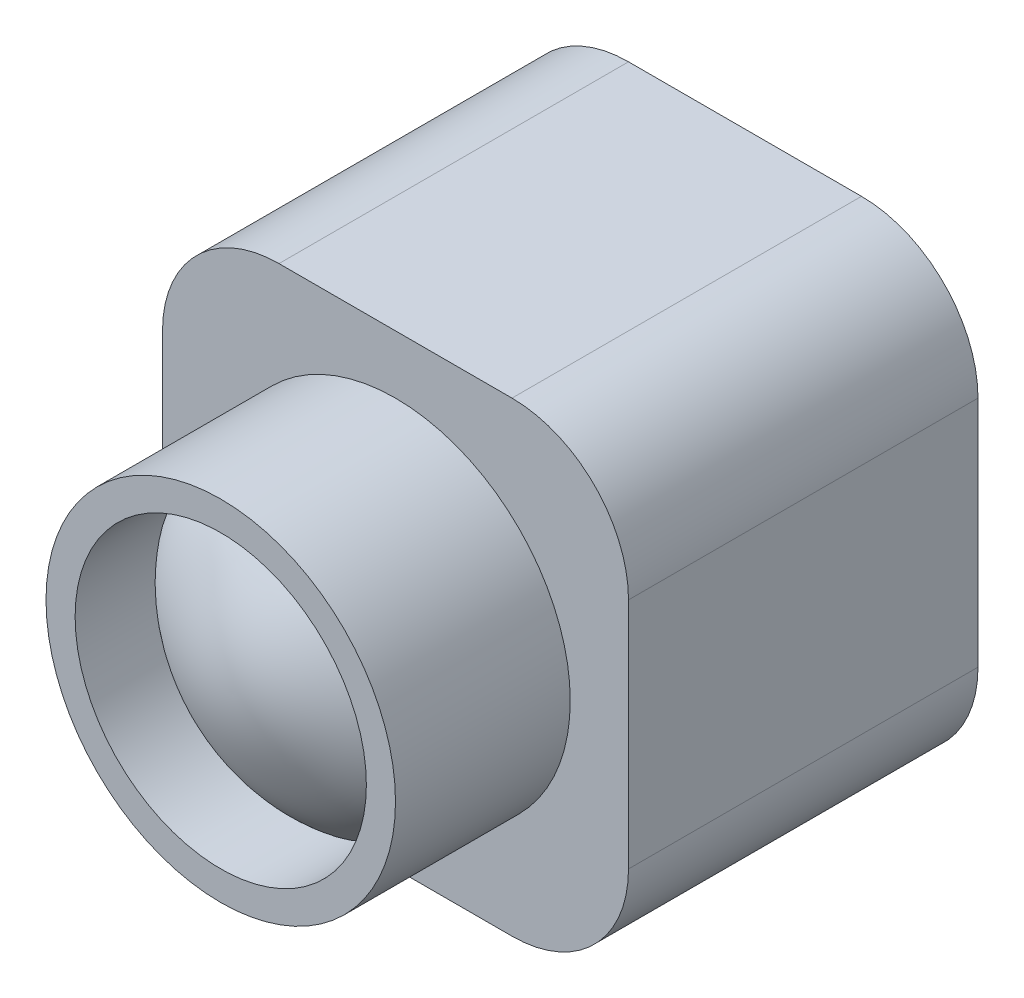
SolidWorks part; units mm, degrees
ref_plane "前视基准面" through (0, 0, 0) normal (0, 0, 1) x (1, 0, 0)
ref_plane "上视基准面" through (0, 0, 0) normal (0, 1, 0) x (1, 0, 0)
ref_plane "右视基准面" through (0, 0, 0) normal (1, 0, 0) x (0, 0, -1)
sketch "草图1" plane through (0, 0, 0) normal (0, 0, 1) x (1, 0, 0)
  line L1 (-10, -20) -> (10, -20)
  line L2 (-20, -10) -> (-20, 10)
  line L3 (-10, 20) -> (10, 20)
  line L4 (20, -10) -> (20, 10)
  line L5 (-20, -20) -> (20, 20) construction
  line L6 (-20, 20) -> (20, -20) construction
  arc A0 (-20, 10) -> (-10, 20) centre (-10, 10) cw
  arc A1 (10, -20) -> (20, -10) centre (10, -10) ccw
  arc A2 (-10, -20) -> (-20, -10) centre (-10, -10) cw
  arc A3 (10, 20) -> (20, 10) centre (10, 10) cw
  point P0 (0, 0)
  dimension "D3" = 10
  dimension "D4" = 10
  dimension "D1" = 40
  dimension "D2" = 40
extrude "凸台-拉伸1" add sketch "草图1" against normal blind 30
sketch "草图2" plane through (0, 0, 0) normal (0, 0, 1) x (1, 0, 0)
  circle A0 centre (0, 0) radius 15
  dimension "D1" = 30
extrude "凸台-拉伸2" add sketch "草图2" along normal blind 15
sketch "草图3" plane through (0, 0, 15) normal (0, 0, 1) x (1, 0, 0)
  circle A0 centre (0, 0) radius 12.5
  dimension "D1" = 25
extrude "切除-拉伸1" cut sketch "草图3" against normal blind 7
sketch "草图4" plane through (0, 0, 0) normal (0, 1, 0) x (1, 0, 0)
  line L0 (-12.5, -8) -> (12.5, -8) construction
  line L1 (0, -8) -> (12.5, -8)
  line L2 (0, -8) -> (0, -14)
  line L3 (0, -20.6217) -> (0, 9.4351) construction
  spline S0 degree 3 poles (0, -14) (2.434, -14.0176) (6.926, -12.4114) (11.0191, -9.9368) (12.5, -8) knots 0 0 0 0 0.499949 1 1 1 1
  point P6 (6.6791, -12.1945)
  point P8 (9.6387, -10.6291)
  point P12 (6.8258, -12.1945)
  point P13 (3.9885, -13.3441)
  dimension "D1" = 6
revolve "旋转1" add sketch "草图4" angle 360 about L3
